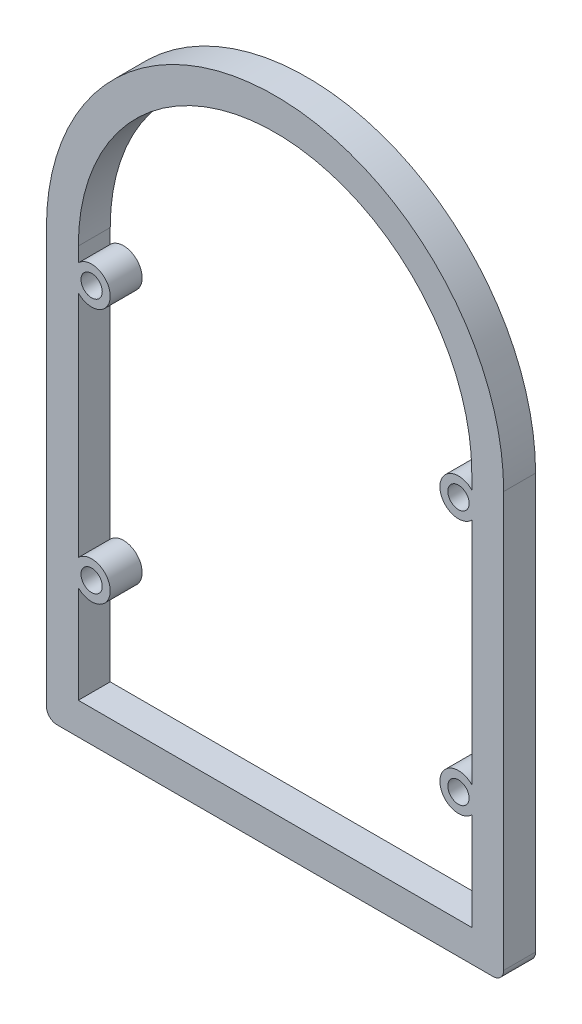
SolidWorks part; units mm, degrees
ref_plane "Front Plane" through (0, 0, 0) normal (0, 0, 1) x (1, 0, 0)
ref_plane "Top Plane" through (0, 0, 0) normal (0, 1, 0) x (1, 0, 0)
ref_plane "Right Plane" through (0, 0, 0) normal (1, 0, 0) x (0, 0, -1)
sketch "Sketch1" plane through (0, 0, 0) normal (0, 0, 1) x (1, 0, 0)
  line L2 (-21.5, 20.5) -> (-21.5, -18.5)
  line L3 (-20.5, -19.5) -> (20.5, -19.5)
  line L4 (21.5, 20.5) -> (21.5, -18.5)
  line L6 (-17.25, 17.9) -> (-17.25, -6.1)
  line L8 (-18.5, 20.5) -> (-18.5, -16.5)
  line L9 (-18.5, -16.5) -> (18.5, -16.5)
  line L10 (18.5, 20.5) -> (18.5, -16.5)
  line L12 (17.25, 17.9) -> (17.25, -6.1)
  arc A0 (-18.5, 20.5) -> (18.5, 20.5) centre (0, 20.5) cw
  arc A1 (-21.5, 20.5) -> (21.5, 20.5) centre (0, 20.5) cw
  arc A2 (-18.5, 16.6753) -> (-18.5, 19.1247) centre (-17.25, 17.9) ccw
  arc A3 (-18.5, -7.3247) -> (-18.5, -4.8753) centre (-17.25, -6.1) ccw
  arc A4 (18.5, 19.1247) -> (18.5, 16.6753) centre (17.25, 17.9) ccw
  arc A5 (18.5, -4.8753) -> (18.5, -7.3247) centre (17.25, -6.1) ccw
  circle A6 centre (-17.25, -6.1) radius 1
  circle A7 centre (-17.25, 17.9) radius 1
  circle A8 centre (17.25, 17.9) radius 1
  circle A9 centre (17.25, -6.1) radius 1
  arc A10 (20.5, -19.5) -> (21.5, -18.5) centre (20.5, -18.5) ccw
  arc A11 (-20.5, -19.5) -> (-21.5, -18.5) centre (-20.5, -18.5) cw
  point P0 (0, 0)
  point P6 (0, 0)
  point P13 (0, 7.5624)
  point P26 (0, 0)
  point P27 (0, 0)
  point P28 (0, 0)
  point P29 (0, 0)
  point P36 (21.5, -19.5)
  point P39 (-21.5, -19.5)
  dimension "D9" = 2
  dimension "D10" = 2
  dimension "D11" = 2
  dimension "D12" = 2
  dimension "D13" = 3.5
  dimension "D14" = 3.5
  dimension "D15" = 3.5
  dimension "D16" = 3.5
  dimension "D19" = 1
  dimension "D1" = 40
  dimension "D2" = 43
  dimension "D3" = 37
  dimension "D4" = 37
  dimension "D5" = 3
  dimension "D6" = 1.25
  dimension "D7" = 1.25
  dimension "D8" = 24
  dimension "D17" = 10.4
  dimension "D18" = 34.5
extrude "Boss-Extrude1" add sketch "Sketch1" along normal blind 3
